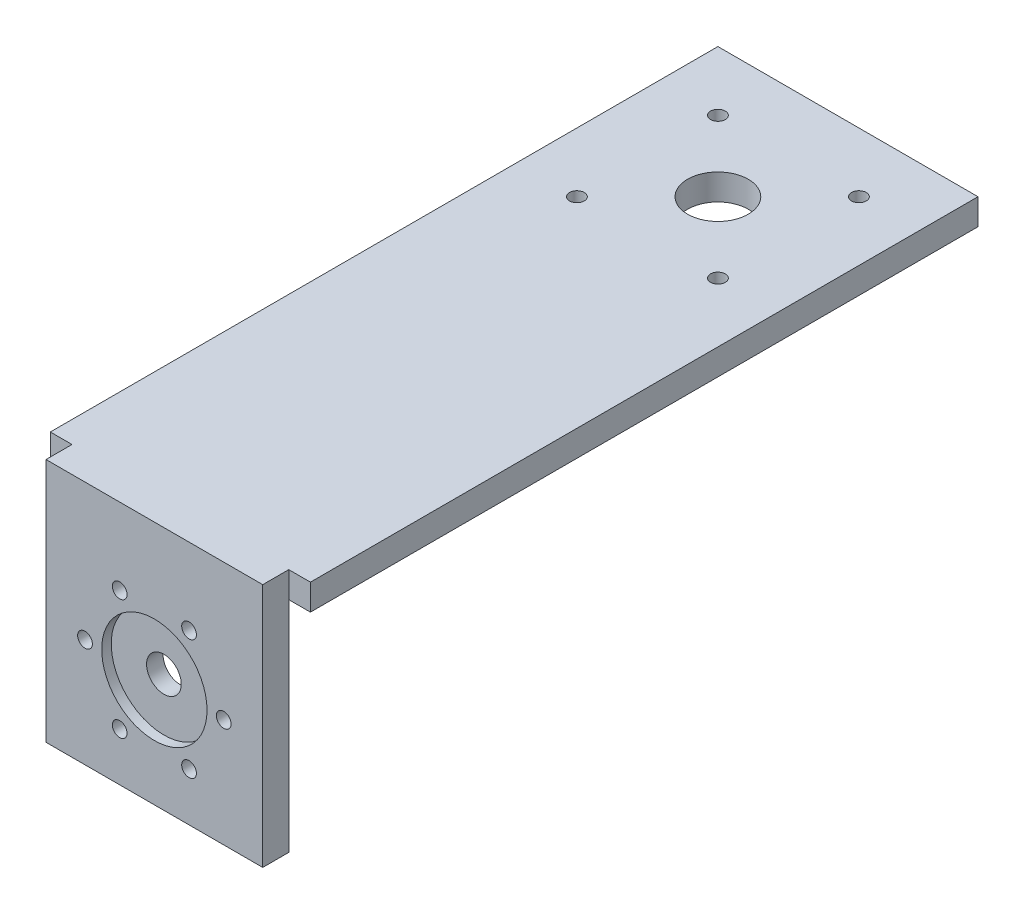
SolidWorks part; units mm, degrees
ref_plane "Front Plane" through (0, 0, 0) normal (0, 0, 1) x (1, 0, 0)
ref_plane "Top Plane" through (0, 0, 0) normal (0, 1, 0) x (1, 0, 0)
ref_plane "Right Plane" through (0, 0, 0) normal (1, 0, 0) x (0, 0, -1)
ref_plane "PL_Yaw_Plate_base" through (0, 0, -6) normal (0, 0, 1) x (1, 0, 0)
sketch "SK_Yaw_Plate" plane through (0, 0, -6) normal (0, 0, 1) x (1, 0, 0)
  line L0 (-25, 31.5) -> (25, 31.5)
  line L1 (25, 31.5) -> (25, -25)
  line L2 (25, -25) -> (-25, -25)
  line L3 (-25, -25) -> (-25, 31.5)
  circle A0 centre (16, 0) radius 1.7
  circle A1 centre (8, -13.8564) radius 1.7
  circle A2 centre (-8, -13.8564) radius 1.7
  circle A3 centre (-16, 0) radius 1.7
  circle A4 centre (-8, 13.8564) radius 1.7
  circle A5 centre (8, 13.8564) radius 1.7
  circle A6 centre (0, 0) radius 4
  dimension "D9_SK_Yaw_Plate" = 3.4
  dimension "D11_SK_Yaw_Plate" = 3.4
  dimension "D14_SK_Yaw_Plate" = 3.4
  dimension "D17_SK_Yaw_Plate" = 3.4
  dimension "D19_SK_Yaw_Plate" = 3.4
  dimension "D22_SK_Yaw_Plate" = 3.4
  dimension "D25_SK_Yaw_Plate" = 8
  dimension "P1" = 25
  dimension "P2" = 31.5
  dimension "P3" = 25
  dimension "P4" = 31.5
  dimension "P5" = 25
  dimension "P6" = 25
  dimension "P7" = 25
  dimension "P8" = 25
  dimension "P10" = 16
  dimension "P12" = 8
  dimension "P13" = 13.8564
  dimension "P15" = 8
  dimension "P16" = 13.8564
  dimension "P18" = 16
  dimension "P20" = 8
  dimension "P21" = 13.8564
  dimension "P23" = 8
  dimension "P24" = 13.8564
extrude "Yaw_Plate" add sketch "SK_Yaw_Plate" along normal blind 6
sketch "SK_Yaw_Pilot_Recess" plane through (0, 0, 0) normal (0, 0, 1) x (1, 0, 0)
  circle A0 centre (0, 0) radius 12.15
  dimension "D1_SK_Yaw_Pilot_Recess" = 24.3
extrude "Yaw_Pilot_Recess" cut sketch "SK_Yaw_Pilot_Recess" against normal blind 2.2
ref_plane "PL_Elbow_Plate_base" through (0, 25.5, 0) normal (0, 1, 0) x (1, 0, 0)
sketch "SK_Elbow_Plate" plane through (0, 25.5, 0) normal (0, 1, 0) x (1, 0, 0)
  line L0 (-30, 6) -> (30, 6)
  line L1 (30, 6) -> (30, 160)
  line L2 (30, 160) -> (-30, 160)
  line L3 (-30, 160) -> (-30, 6)
  circle A0 centre (16.2635, 146.2635) radius 1.7
  circle A1 centre (-16.2635, 146.2635) radius 1.7
  circle A2 centre (-16.2635, 113.7365) radius 1.7
  circle A3 centre (16.2635, 113.7365) radius 1.7
  circle A4 centre (0, 130) radius 7
  dimension "D9_SK_Elbow_Plate" = 3.4
  dimension "D12_SK_Elbow_Plate" = 3.4
  dimension "D15_SK_Elbow_Plate" = 3.4
  dimension "D18_SK_Elbow_Plate" = 3.4
  dimension "D21_SK_Elbow_Plate" = 14
  dimension "P1" = 30
  dimension "P2" = 6
  dimension "P3" = 30
  dimension "P4" = 6
  dimension "P5" = 30
  dimension "P6" = 160
  dimension "P7" = 30
  dimension "P8" = 160
  dimension "P10" = 16.2635
  dimension "P11" = 146.2635
  dimension "P13" = 16.2635
  dimension "P14" = 146.2635
  dimension "P16" = 16.2635
  dimension "P17" = 113.7365
  dimension "P19" = 16.2635
  dimension "P20" = 113.7365
  dimension "P22" = 130
extrude "Elbow_Plate" add sketch "SK_Elbow_Plate" along normal blind 6
equation "\"Elbow_z\" = -130"
